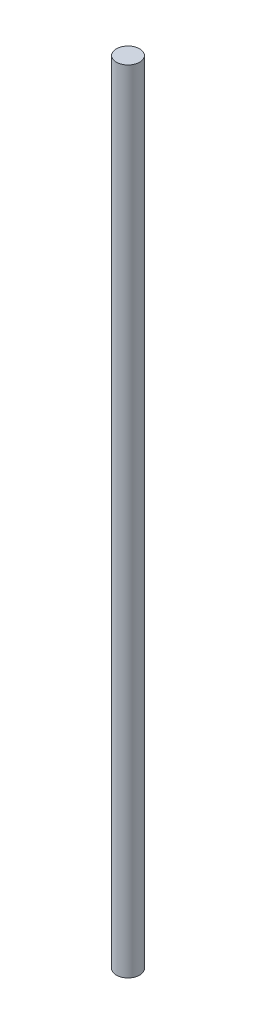
SolidWorks part; units mm, degrees
material "Ductile Iron"
ref_plane "Front Plane" through (0, 0, 0) normal (0, 0, 1) x (1, 0, 0)
ref_plane "Top Plane" through (0, 0, 0) normal (0, 1, 0) x (1, 0, 0)
ref_plane "Right Plane" through (0, 0, 0) normal (1, 0, 0) x (0, 0, -1)
sketch "Sketch1" plane through (0, 0, 0) normal (0, 1, 0) x (1, 0, 0)
  circle A0 centre (0, 0) radius 5
  dimension "D1" = 10
extrude "Boss-Extrude1" add sketch "Sketch1" along normal blind 300
sketch "Sketch2" plane through (0, 0, 0) normal (0, -1, 0) x (1, 0, 0)
  circle A0 centre (0, 0) radius 5
extrude "Boss-Extrude2" add sketch "Sketch2" along normal blind 20
sketch "Sketch3" plane through (0, 300, 0) normal (0, 1, 0) x (1, 0, 0)
  circle A0 centre (0, 0) radius 5
extrude "Boss-Extrude3" add sketch "Sketch3" along normal blind 20
